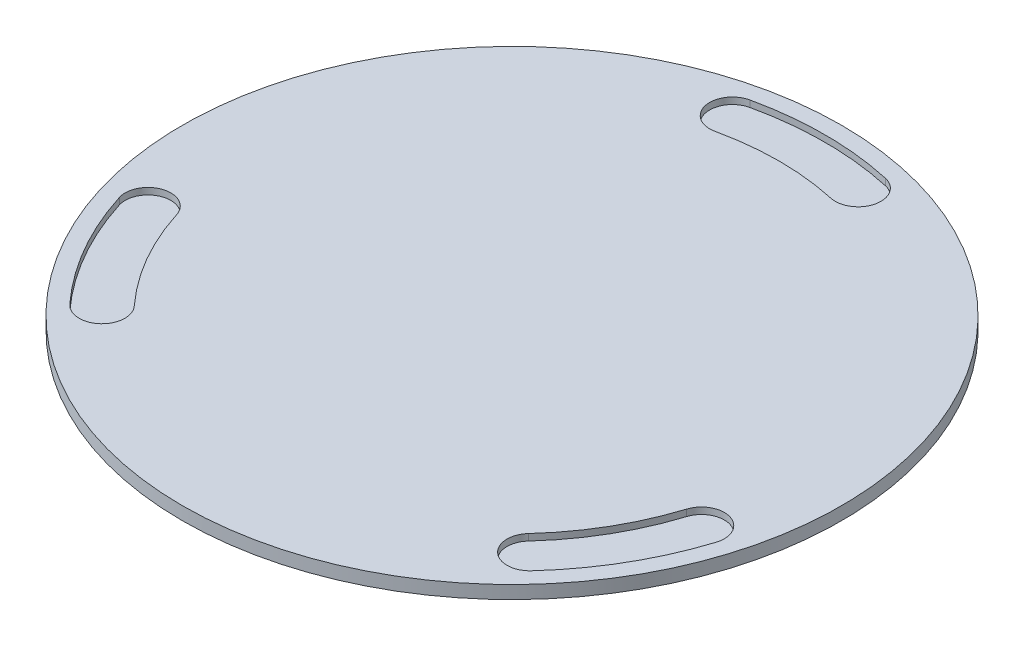
SolidWorks part; units mm, degrees
ref_plane "Front Plane" through (0, 0, 0) normal (0, 0, 1) x (1, 0, 0)
ref_plane "Top Plane" through (0, 0, 0) normal (0, 1, 0) x (1, 0, 0)
ref_plane "Right Plane" through (0, 0, 0) normal (1, 0, 0) x (0, 0, -1)
sketch "Sketch1" plane through (0, 0, 0) normal (0, 1, 0) x (1, 0, 0)
  circle A0 centre (0, 0) radius 50.5
  dimension "D1" = 101
extrude "Boss-Extrude1" add sketch "Sketch1" along normal mid plane 2
sketch "Sketch2" plane through (0, 1, 0) normal (0, 1, 0) x (1, 0, 0)
  line L0 (-9.6239, 43.4105) -> (0, 0) construction
  line L1 (0, 0) -> (9.6239, 43.4105) construction
  arc A0 (-9.6239, 43.4105) -> (9.6239, 43.4105) centre (0, 0) cw construction
  arc A1 (10.2732, 46.3394) -> (-10.2732, 46.3394) centre (0, 0) ccw construction
  arc A2 (8.9746, 40.4816) -> (-8.9746, 40.4816) centre (0, 0) ccw construction
  arc A3 (8.9746, 40.4816) -> (10.2732, 46.3394) centre (9.6239, 43.4105) ccw construction
  arc A4 (-10.2732, 46.3394) -> (-8.9746, 40.4816) centre (-9.6239, 43.4105) ccw construction
  arc A5 (10.3814, 46.8275) -> (-10.3814, 46.8275) centre (0, 0) ccw
  arc A6 (-10.3814, 46.8275) -> (-8.8663, 39.9934) centre (-9.6239, 43.4105) ccw
  arc A7 (8.8663, 39.9934) -> (-8.8663, 39.9934) centre (0, 0) ccw
  arc A8 (8.8663, 39.9934) -> (10.3814, 46.8275) centre (9.6239, 43.4105) ccw
  point P4 (0, 44.4645)
  point P11 (0, 0)
  point P13 (0, 0)
  dimension "D2" = 3
  dimension "D1" = 25
  dimension "D3" = 44.4645
  dimension "D4" = 0.5
extrude "Cut-Extrude1" cut sketch "Sketch2" against normal blind 1
pattern_circular "CirPattern1" count 3 over 360 about axis through (0, 0, 0) along (0, 1, 0) of "Cut-Extrude1"
